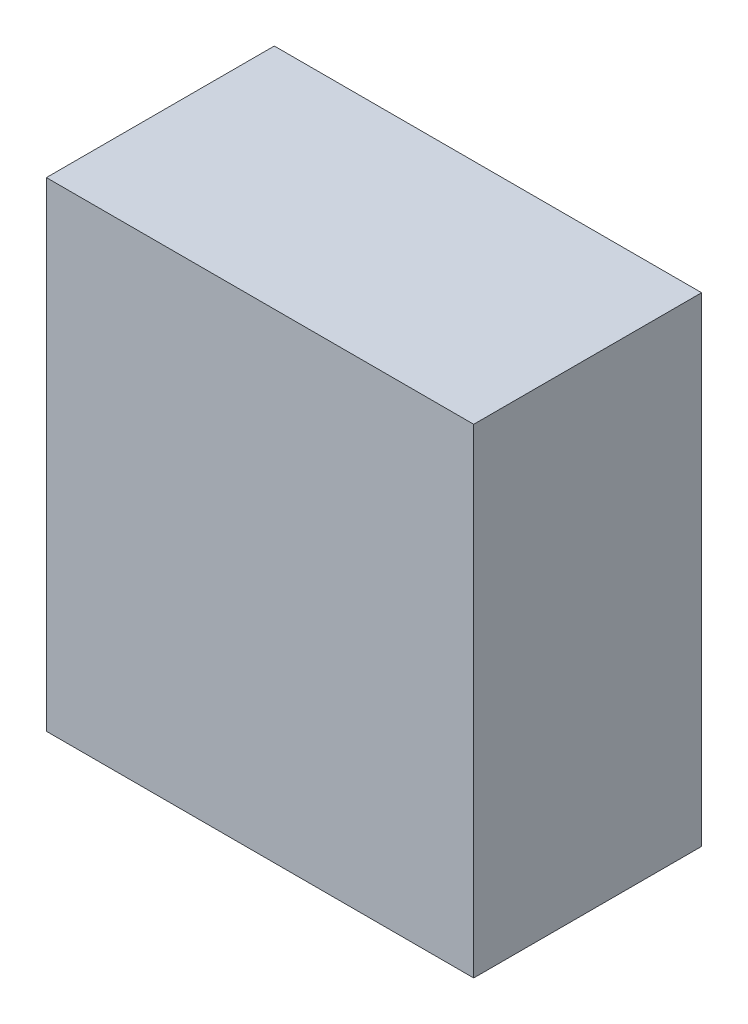
SolidWorks part; units mm, degrees
material "ABS"
ref_plane "Front Plane" through (0, 0, 0) normal (0, 0, 1) x (1, 0, 0)
ref_plane "Top Plane" through (0, 0, 0) normal (0, 1, 0) x (1, 0, 0)
ref_plane "Right Plane" through (0, 0, 0) normal (1, 0, 0) x (0, 0, -1)
sketch "Sketch1" plane through (0, 0, 0) normal (0, 0, 1) x (1, 0, 0)
  line L1 (4.5, -5.05) -> (-4.5, -5.05)
  line L2 (4.5, -5.05) -> (4.5, 5.05)
  line L3 (4.5, 5.05) -> (-4.5, 5.05)
  line L4 (-4.5, -5.05) -> (-4.5, 5.05)
  line L5 (4.5, -5.05) -> (-4.5, 5.05) construction
  line L6 (4.5, 5.05) -> (-4.5, -5.05) construction
  point P0 (0, 0)
  dimension "D1" = 10.1
  dimension "D2" = 9
extrude "Boss-Extrude1" add sketch "Sketch1" along normal blind 4.8
